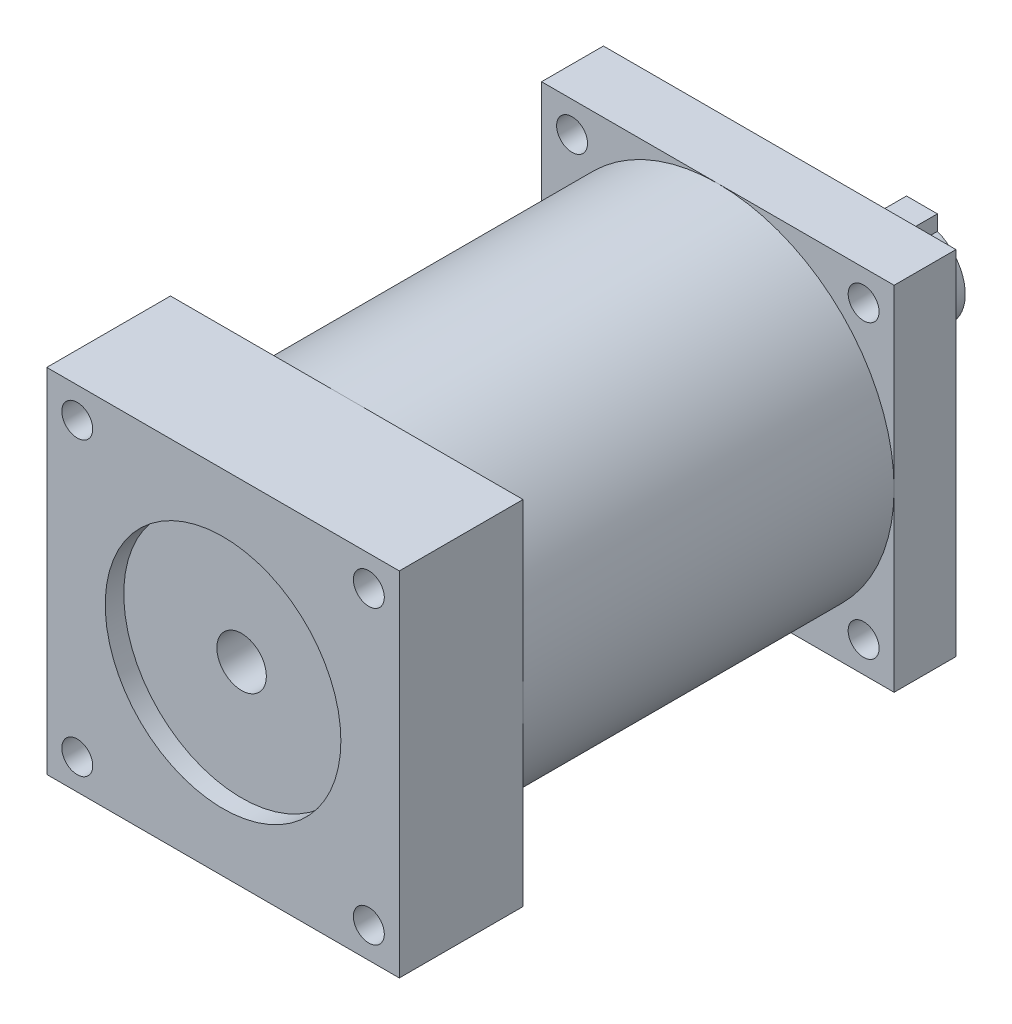
SolidWorks part; units mm, degrees
ref_plane "前视基准面" through (0, 0, 0) normal (0, 0, 1) x (1, 0, 0)
ref_plane "上视基准面" through (0, 0, 0) normal (0, 1, 0) x (1, 0, 0)
ref_plane "右视基准面" through (0, 0, 0) normal (1, 0, 0) x (0, 0, -1)
sketch "草图1" plane through (0, 0, 0) normal (0, 0, 1) x (1, 0, 0)
  line L1 (-23.57, 23.57) -> (23.57, 23.57) construction
  line L2 (-23.57, 23.57) -> (-23.57, -23.57) construction
  line L3 (-23.57, -23.57) -> (23.57, -23.57) construction
  line L4 (23.57, 23.57) -> (23.57, -23.57) construction
  line L5 (-23.57, 23.57) -> (23.57, -23.57) construction
  line L6 (-23.57, -23.57) -> (23.57, 23.57) construction
  line L7 (-28.5, 28.5) -> (28.5, 28.5)
  line L8 (-28.5, 28.5) -> (-28.5, -28.5)
  line L9 (-28.5, -28.5) -> (28.5, -28.5)
  line L10 (28.5, 28.5) -> (28.5, -28.5)
  line L11 (-28.5, 28.5) -> (28.5, -28.5) construction
  line L12 (-28.5, -28.5) -> (28.5, 28.5) construction
  circle A0 centre (-23.57, 23.57) radius 2.5
  circle A1 centre (23.57, 23.57) radius 2.5
  circle A2 centre (23.57, -23.57) radius 2.5
  circle A3 centre (-23.57, -23.57) radius 2.5
  point P0 (0, 0)
  point P7 (0, 0)
  dimension "D2" = 5
  dimension "D1" = 47.14
  dimension "D4" = 57
  dimension "D3" = 4
extrude "凸台-拉伸1" add sketch "草图1" along normal blind 90
ref_plane "基准面1" through (0, 0, 45) normal (0, 0, -1) x (-1, 0, 0)
sketch "草图2" plane through (0, 0, 45) normal (0, 0, -1) x (-1, 0, 0)
  line L5 (54.214, -56.3664) -> (-54.214, -56.3664)
  line L6 (54.214, -56.3664) -> (54.214, 56.3664)
  line L7 (54.214, 56.3664) -> (-54.214, 56.3664)
  line L8 (-54.214, -56.3664) -> (-54.214, 56.3664)
  line L9 (54.214, -56.3664) -> (-54.214, 56.3664) construction
  line L10 (54.214, 56.3664) -> (-54.214, -56.3664) construction
  circle A0 centre (0, 0) radius 28.5
  dimension "D1" = 57
extrude "切除-拉伸1" cut sketch "草图2" against normal blind 25 and the other way blind 35 contours L7 L8 L5 L6
sketch "草图3" plane through (0, 0, 0) normal (0, 0, -1) x (-1, 0, 0)
  circle A0 centre (0, 0) radius 21
  dimension "D1" = 42
extrude "凸台-拉伸2" add sketch "草图3" along normal blind 3
sketch "草图4" plane through (0, 0, -3) normal (0, 0, -1) x (-1, 0, 0)
  circle A0 centre (0, 0) radius 7
  dimension "D1" = 14
extrude "凸台-拉伸3" add sketch "草图4" along normal blind 20
sketch "草图5" plane through (0, 0, 90) normal (0, 0, 1) x (1, 0, 0)
  circle A0 centre (0, 0) radius 4
  dimension "D1" = 8
extrude "切除-拉伸2" cut sketch "草图5" against normal blind 26
sketch "草图6" plane through (0, 0, 90) normal (0, 0, 1) x (1, 0, 0)
  circle A0 centre (0, 0) radius 19.05
  dimension "D1" = 38.1
extrude "切除-拉伸3" cut sketch "草图6" against normal blind 3
sketch "草图7" plane through (0, 0, -23) normal (0, 0, -1) x (-1, 0, 0)
  line L0 (0, 0) -> (0, 9) construction
  line L1 (0, 9) -> (2.5, 9)
  line L2 (0, 9) -> (-2.5, 9)
  line L3 (-2.5, 9) -> (-2.5, 0)
  line L4 (-2.5, 0) -> (2.5, 0)
  line L5 (2.5, 0) -> (2.5, 9)
extrude "凸台-拉伸4" add sketch "草图7" against normal blind 18
